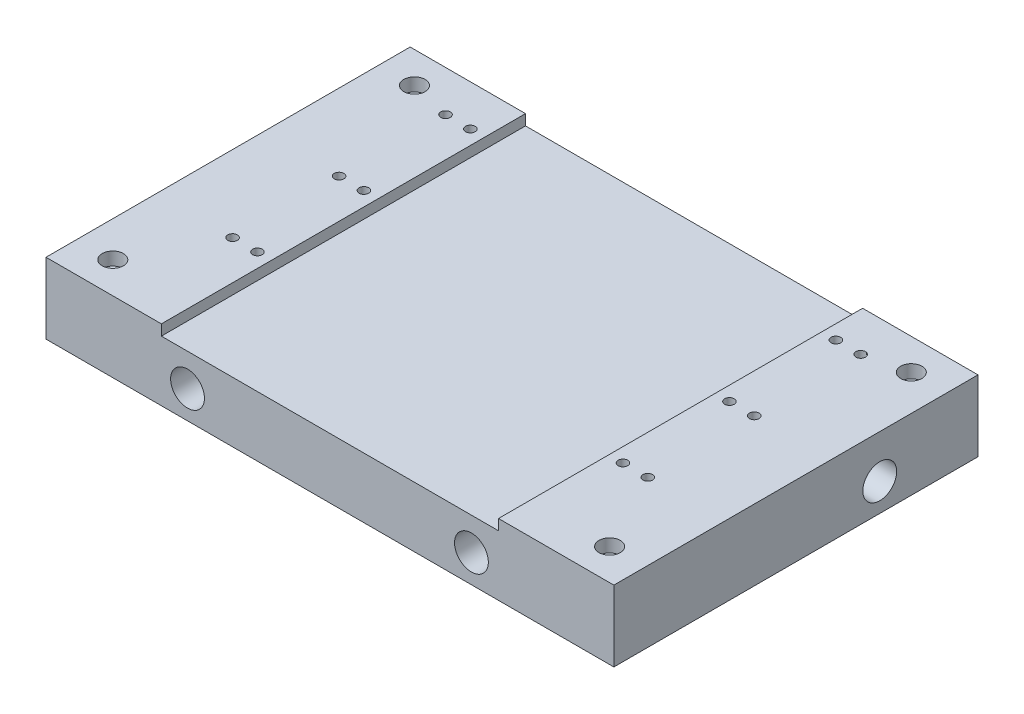
SolidWorks part; units mm, degrees
material "6061 Alloy"
ref_plane "Front Plane" through (0, 0, 0) normal (0, 0, 1) x (1, 0, 0)
ref_plane "Top Plane" through (0, 0, 0) normal (0, 1, 0) x (1, 0, 0)
ref_plane "Right Plane" through (0, 0, 0) normal (1, 0, 0) x (0, 0, -1)
sketch "Sketch1" plane through (0, 0, 0) normal (0, 1, 0) x (1, 0, 0)
  line L1 (0, 0) -> (160.02, 0)
  line L2 (0, 0) -> (0, 102.616)
  line L3 (0, 102.616) -> (160.02, 102.616)
  line L4 (160.02, 0) -> (160.02, 102.616)
  dimension "D1" = 160.02
  dimension "D2" = 102.616
extrude "body" add sketch "Sketch1" along normal blind 19.9898
hole_wizard "CBORE for #6 Socket Head Cap Screw1" positions "Sketch3" profile "Sketch2" counterbore size "#6" standard "ANSI Inch" end condition through all
sketch "Sketch3" plane through (0, 19.9898, 0) normal (0, 1, 0) x (1, 0, 0)
  line L1 (10.0076, 93.8276) -> (150.0124, 93.8276) construction
  line L2 (10.0076, 93.8276) -> (10.0076, 8.8138) construction
  line L3 (10.0076, 8.8138) -> (150.0124, 8.8138) construction
  line L4 (150.0124, 93.8276) -> (150.0124, 8.8138) construction
  line L5 (0, 102.616) -> (0, 0) construction
  line L6 (160.02, 102.616) -> (0, 102.616) construction
  point P1 (10.0076, 93.8276)
  point P2 (150.0124, 8.8138)
  point P5 (10.0076, 8.8138)
  point P6 (150.0124, 93.8276)
  dimension "D1" = 10.0076
  dimension "D2" = 150.0124
  dimension "D3" = 93.8022
  dimension "D4" = 8.7884
sketch "Sketch2" plane through (10.0076, 19.9898, -93.8276) normal (1, 0, 0) x (0, 0, 1)
  line L0 (0, 0) -> (0, 19.9898)
  line L1 (0, 19.9898) -> (1.8987, 19.9898)
  line L3 (1.8987, 19.9898) -> (1.8987, 3.683)
  line L4 (1.8987, 3.683) -> (2.9972, 3.683)
  line L5 (2.9972, 3.683) -> (2.9972, 0)
  line L7 (2.9972, 0) -> (0, 0)
  line L11 (0, -6.35) -> (0, 107.95) construction
  dimension "Thru Hole Dia." = 3.7973
  dimension "Thru Hole Depth" = 19.9898
  dimension "C'Bore Dia." = 5.9944
  dimension "C'Bore Depth" = 3.683
hole_wizard "Tap Drill for #6-32 Tap1" positions "Sketch5" profile "Sketch4" hole size "#6-32" standard "ANSI Inch" end condition through all
sketch "Sketch5" plane through (0, 19.9898, 0) normal (0, 1, 0) x (1, 0, 0)
  line L0 (28.5, 91.0844) -> (28.5, 31.0844) construction
  line L3 (0, 102.616) -> (0, 0) construction
  line L4 (160.02, 102.616) -> (0, 102.616) construction
  line L8 (131.5, 91.0844) -> (131.5, 31.0844) construction
  line L9 (131.5, 91.0844) -> (28.5, 91.0844) construction
  line L10 (28.5, 91.0844) -> (21.5, 91.0844) construction
  line L12 (28.5, 61.0844) -> (21.5, 61.0844) construction
  line L14 (28.5, 31.0844) -> (21.5, 31.0844) construction
  line L16 (131.5, 91.0844) -> (138.5, 91.0844) construction
  line L18 (131.5, 61.0844) -> (138.5, 61.0844) construction
  line L20 (131.5, 31.0844) -> (138.5, 31.0844) construction
  point P1 (28.5, 91.0844)
  point P2 (28.5, 31.0844)
  point P15 (28.5, 61.0844)
  point P22 (131.5, 91.0844)
  point P23 (131.5, 31.0844)
  point P24 (131.5, 61.0844)
  point P64 (21.5, 91.0844)
  point P67 (21.5, 61.0844)
  point P70 (21.5, 31.0844)
  point P73 (138.5, 31.0844)
  point P76 (138.5, 61.0844)
  point P79 (138.5, 91.0844)
  dimension "D1" = 28.5
  dimension "D2" = 11.5316
  dimension "D3" = 7
  dimension "D5" = 103
  dimension "D8" = 30
sketch "Sketch4" plane through (28.5, 19.9898, -91.0844) normal (1, 0, 0) x (0, 0, 1)
  line L0 (0, 0) -> (0, 19.9898)
  line L1 (0, 19.9898) -> (1.3525, 19.9898)
  line L2 (1.3525, 19.9898) -> (1.3525, 0)
  line L5 (1.3525, 0) -> (0, 0)
  line L11 (0, -6.35) -> (0, 107.95) construction
  dimension "Thru Hole Dia." = 2.7051
  dimension "Thru Hole Depth" = 19.9898
sketch "Sketch6" plane through (0, 19.9898, 0) normal (0, 1, 0) x (1, 0, 0)
  line L0 (160.02, 102.616) -> (0, 102.616) construction
  line L1 (32.512, 102.616) -> (127.512, 102.616)
  line L2 (32.512, 102.616) -> (32.512, 0)
  line L3 (0, 0) -> (160.02, 0) construction
  line L4 (127.512, 102.616) -> (127.512, 0)
  line L5 (0, 102.616) -> (0, 0) construction
  line L6 (32.512, 0) -> (127.512, 0)
  dimension "D1" = 32.512
  dimension "D2" = 95
extrude "gouge" cut sketch "Sketch6" against normal blind 2.9972
sketch "Sketch7" plane through (0, 0, 0) normal (0, 0, 1) x (1, 0, 0)
  line L0 (0, 7.874) -> (160.02, 7.874) construction
  line L1 (0, 19.9898) -> (0, 0) construction
  line L2 (160.02, 19.9898) -> (160.02, 0) construction
  line L3 (0, 0) -> (160.02, 0) construction
  circle A0 centre (39.878, 7.874) radius 4.572
  circle A1 centre (119.888, 7.874) radius 4.572
  dimension "D2" = 39.878
  dimension "D4" = 9.144
  dimension "D5" = 9.144
  dimension "D1" = 7.874
  dimension "D3" = 119.888
extrude "pipes1" cut sketch "Sketch7" against normal blind 80.01
sketch "Sketch8" plane through (160.02, 0, 0) normal (1, 0, 0) x (0, 0, -1)
  line L0 (0, 7.874) -> (102.616, 7.874) construction
  line L1 (0, 19.9898) -> (0, 0) construction
  line L2 (102.616, 19.9898) -> (102.616, 0) construction
  line L3 (0, 0) -> (102.616, 0) construction
  circle A0 centre (74.93, 7.874) radius 4.572
  dimension "D2" = 74.93
  dimension "D3" = 9.144
  dimension "D1" = 7.874
extrude "pipes2" cut sketch "Sketch8" against normal blind 119.888
hole_wizard "Pipe Tap Drill for 1/8 Tap2" positions "Sketch10" profile "Sketch9" hole size "1/8" standard "ANSI Inch"
sketch "Sketch10" plane through (0, 0, 0) normal (0, 0, 1) x (1, 0, 0)
  point P0 (39.878, 7.874)
  point P3 (119.888, 7.874)
sketch "Sketch9" plane through (39.878, 7.874, 0) normal (1, 0, 0) x (0, -1, 0)
  line L0 (0, 0) -> (0, 22.9276)
  line L1 (0, 22.9276) -> (4.7625, 20.066)
  line L2 (4.7625, 20.066) -> (4.7625, 0)
  line L5 (4.7625, 0) -> (0, 0)
  line L10 (0, 22.9276) -> (-4.7625, 20.066) construction
  line L11 (0, -6.35) -> (0, 107.95) construction
  dimension "Hole Dia." = 9.525
  dimension "Hole Depth" = 20.066
  dimension "Drill Angle" = 118
hole_wizard "Pipe Tap Drill for 1/8 Tap3" positions "Sketch12" profile "Sketch11" hole size "1/8" standard "ANSI Inch"
sketch "Sketch12" plane through (160.02, 0, 0) normal (1, 0, 0) x (0, 0, -1)
  point P0 (74.93, 7.874)
sketch "Sketch11" plane through (160.02, 7.874, -74.93) normal (0, 1, 0) x (0, 0, -1)
  line L0 (0, 0) -> (0, 22.9276)
  line L1 (0, 22.9276) -> (4.7625, 20.066)
  line L2 (4.7625, 20.066) -> (4.7625, 0)
  line L5 (4.7625, 0) -> (0, 0)
  line L10 (0, 22.9276) -> (-4.7625, 20.066) construction
  line L11 (0, -6.35) -> (0, 107.95) construction
  dimension "Hole Dia." = 9.525
  dimension "Hole Depth" = 20.066
  dimension "Drill Angle" = 118
